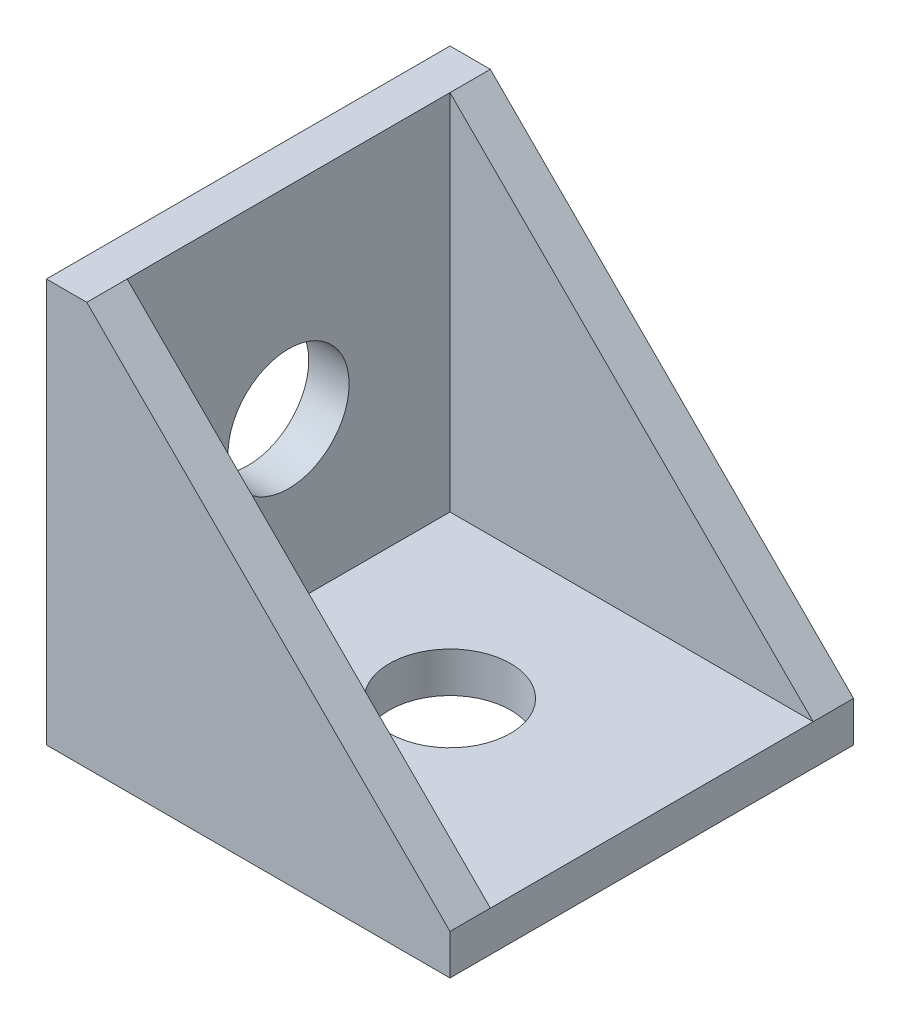
SolidWorks part; units mm, degrees
material "6063-T6"
ref_plane "Front Plane" through (0, 0, 0) normal (0, 0, 1) x (1, 0, 0)
ref_plane "Top Plane" through (0, 0, 0) normal (0, 1, 0) x (1, 0, 0)
ref_plane "Right Plane" through (0, 0, 0) normal (1, 0, 0) x (0, 0, -1)
sketch "Sketch1" plane through (0, 0, 0) normal (0, 0, 1) x (1, 0, 0)
  line L0 (20, 0) -> (0, 0)
  line L1 (0, 0) -> (0, 20)
  line L2 (0, 20) -> (2, 20)
  line L3 (2, 20) -> (20, 2)
  line L4 (20, 2) -> (20, 0)
  dimension "D1" = 20
  dimension "D2" = 2
extrude "Boss-Extrude1" add sketch "Sketch1" along normal mid plane 20
sketch "Sketch2" plane through (0, 20, 0) normal (0, 1, 0) x (1, 0, 0)
  line L0 (2, -10) -> (2, 10) construction
  line L1 (20, -8) -> (2, -8)
  line L2 (20, -8) -> (20, 8)
  line L3 (20, 8) -> (2, 8)
  line L4 (2, -8) -> (2, 8)
  line L5 (11, 8) -> (11, -8) construction
  line L6 (20, 0) -> (2, 0) construction
  line L7 (20, -10) -> (20, 10) construction
  line L8 (2, 8) -> (2, 10) construction
  line L9 (2, 8) -> (0, 8) construction
  line L10 (0, -10) -> (0, 10) construction
  point P0 (11, 0)
extrude "Cut-Extrude1" cut sketch "Sketch2" against normal up to vertex (18 mm away)
sketch "Sketch3" plane through (2, 0, 0) normal (1, 0, 0) x (0, 0, -1)
  line L0 (0, 0) -> (0, 10) construction
  circle A0 centre (0, 10) radius 3
  dimension "D2" = 6
  dimension "D1" = 10
extrude "Cut-Extrude2" cut sketch "Sketch3" against normal blind 20
sketch "Sketch4" plane through (0, 2, 0) normal (0, 1, 0) x (1, 0, 0)
  line L0 (0, 0) -> (10, 0) construction
  line L1 (0, -10) -> (0, 10) construction
  circle A0 centre (10, 0) radius 3
  dimension "D1" = 6
  dimension "D2" = 10
extrude "Cut-Extrude3" cut sketch "Sketch4" against normal blind 20
